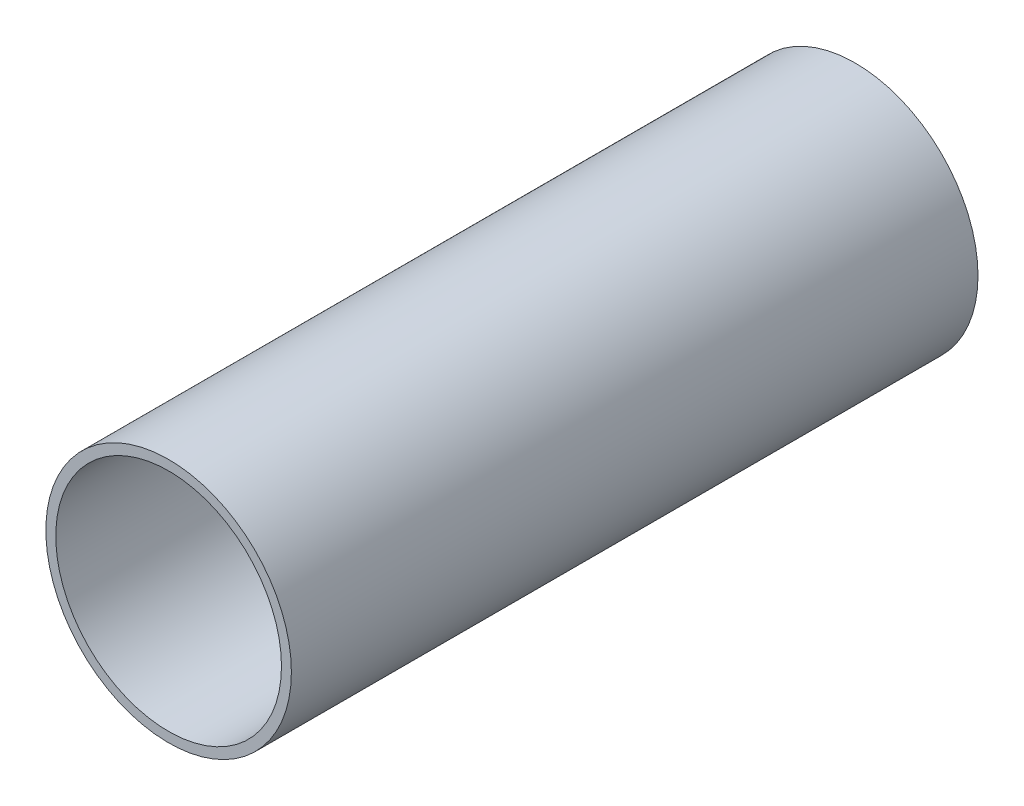
SolidWorks part; units mm, degrees
ref_plane "Front Plane" through (0, 0, 0) normal (0, 0, 1) x (1, 0, 0)
ref_plane "Top Plane" through (0, 0, 0) normal (0, 1, 0) x (1, 0, 0)
ref_plane "Right Plane" through (0, 0, 0) normal (1, 0, 0) x (0, 0, -1)
sketch "Sketch1" plane through (0, 0, 0) normal (0, 0, 1) x (1, 0, 0)
  circle A0 centre (0, 0) radius 109
  circle A1 centre (0, 0) radius 100.2
  dimension "D1" = 218
  dimension "D2" = 8.8
extrude "Boss-Extrude1" add sketch "Sketch1" along normal blind 609.6
